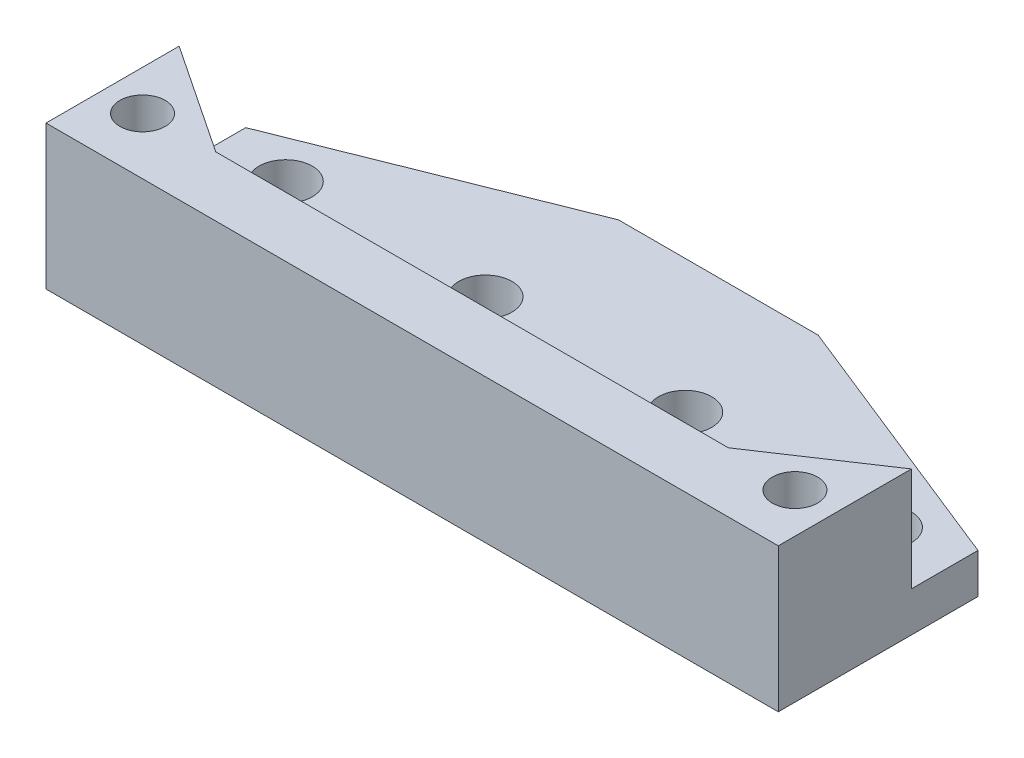
SolidWorks part; units mm, degrees
ref_plane "Front Plane" through (0, 0, 0) normal (0, 0, 1) x (1, 0, 0)
ref_plane "Top Plane" through (0, 0, 0) normal (0, 1, 0) x (1, 0, 0)
ref_plane "Right Plane" through (0, 0, 0) normal (1, 0, 0) x (0, 0, -1)
sketch "Sketch2" plane through (0, 0, 0) normal (0, 1, 0) x (1, 0, 0)
  line L0 (0, 0) -> (0, 15)
  line L1 (0, 15) -> (20, 23)
  line L2 (20, 23) -> (35, 23)
  line L3 (35, 23) -> (55, 15)
  line L4 (55, 15) -> (55, 0)
  line L5 (55, 0) -> (0, 0)
  line L6 (20, 13) -> (35, 13) construction
  line L7 (27.5, 23) -> (27.5, 0) construction
  circle A0 centre (5, 13) radius 2
  circle A1 centre (20, 13) radius 2
  circle A2 centre (35, 13) radius 2
  circle A3 centre (50, 13) radius 2
  point P17 (27.5, 13)
  dimension "D5" = 4
  dimension "D7" = 15
  dimension "D8" = 15
  dimension "D9" = 15
  dimension "D1" = 55
  dimension "D2" = 15
  dimension "D3" = 15
  dimension "D4" = 8
  dimension "D6" = 13
extrude "Boss-Extrude1" add sketch "Sketch2" along normal blind 3
sketch "Sketch3" plane through (0, 3, 0) normal (0, 1, 0) x (1, 0, 0)
  line L0 (0, 0) -> (0, 10)
  line L1 (0, 15) -> (0, 0) construction
  line L2 (0, 10) -> (15, 0)
  line L3 (0, 0) -> (55, 0) construction
  line L4 (15, 0) -> (0, 0)
  line L5 (55, 0) -> (55, 10)
  line L6 (55, 0) -> (55, 15) construction
  line L7 (55, 10) -> (40, 0)
  line L8 (40, 0) -> (55, 0)
  line L9 (46.75, 4.5) -> (8.25, 4.5)
  line M8 (0, 0) -> (55, 0)
  line M9 (55, 0) -> (55, 15)
  line M13 (0, 15) -> (0, 0)
  dimension "D1" = 15
  dimension "D2" = 10
  dimension "D3" = 4.5
extrude "Boss-Extrude2" add sketch "Sketch3" along normal blind 7.8 contours L2 M13 M8 | L7 L9 L2 M8 | L7 M9 M8
sketch "Sketch4" plane through (0, 10.8, 0) normal (0, 1, 0) x (1, 0, 0)
  line L0 (0, 0) -> (55, 0) construction
  line L1 (0, 10) -> (0, 0) construction
  line L2 (55, 0) -> (55, 10) construction
  circle A0 centre (3, 4.25) radius 1.7
  circle A1 centre (52, 4.25) radius 1.7
  point P4 (0, 0)
  dimension "D1" = 3.4
  dimension "D2" = 4.25
  dimension "D3" = 3
  dimension "D4" = 3
extrude "Cut-Extrude1" cut sketch "Sketch4" against normal through all
